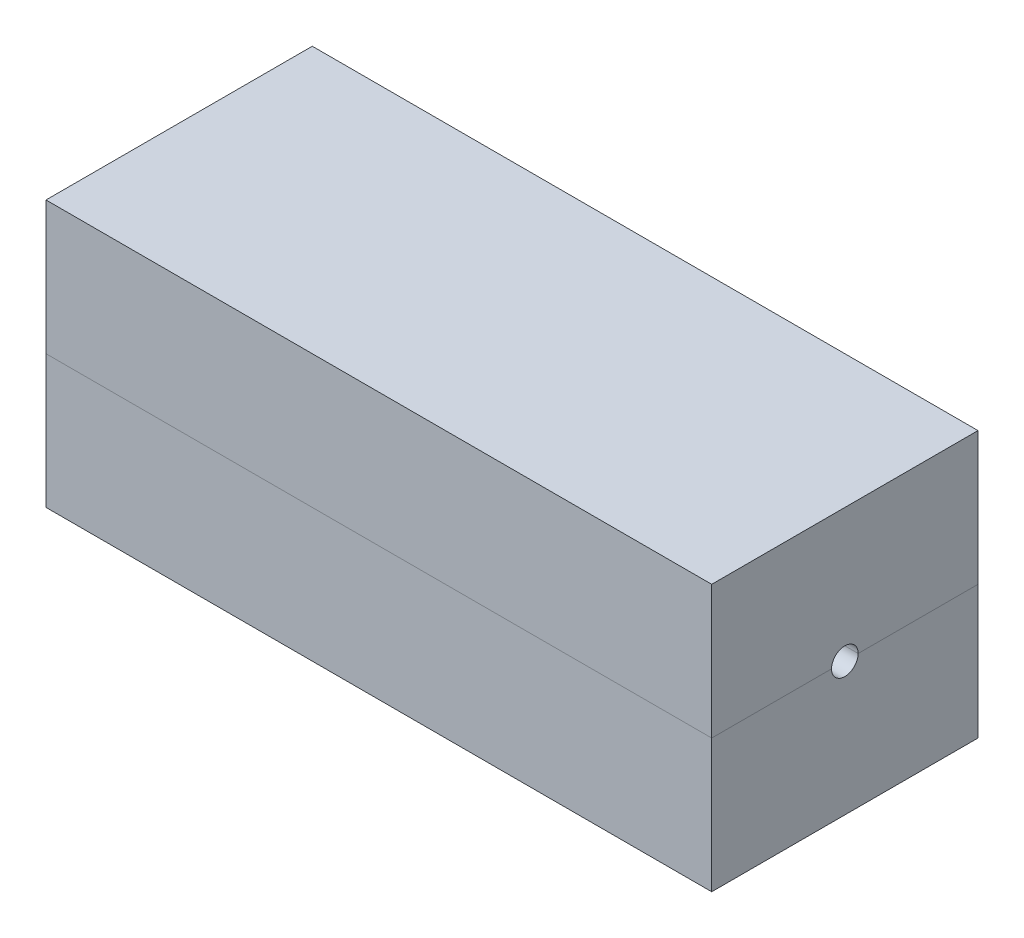
SolidWorks part; units mm, degrees
ref_plane "正面" through (0, 0, 0) normal (0, 0, 1) x (1, 0, 0)
ref_plane "平面" through (0, 0, 0) normal (0, 1, 0) x (1, 0, 0)
ref_plane "右側面" through (0, 0, 0) normal (1, 0, 0) x (0, 0, -1)
sketch "ｽｹｯﾁ1" plane through (0, 0, 0) normal (0, 0, 1) x (1, 0, 0)
  line L1 (0, 0) -> (100, 0)
  line L2 (0, 0) -> (0, 40)
  line L3 (0, 40) -> (100, 40)
  line L4 (100, 0) -> (100, 40)
  dimension "D1" = 40
  dimension "D2" = 100
extrude "ﾎﾞｽ - 押し出し1" add sketch "ｽｹｯﾁ1" along normal blind 40
ref_plane "平面1" through (0, 20, 0) normal (0, 1, 0) x (1, 0, 0)
split "部品分割1" trim tools "平面1" bodies to split 101 resulting bodies 102 103
sketch "ｽｹｯﾁ2" plane through (0, 20, 0) normal (0, 1, 0) x (1, 0, 0)
  line L0 (0, -20) -> (100, -20) construction
  line L1 (0, -40) -> (0, 0) construction
  line L2 (100, -40) -> (100, 0) construction
  line L4 (10, -30) -> (90, -30)
  line L5 (10, -30) -> (10, -10)
  line L6 (10, -10) -> (90, -10)
  line L7 (90, -30) -> (90, -10)
  line L8 (10, -30) -> (90, -10) construction
  line L9 (10, -10) -> (90, -30) construction
  point P6 (50, -20)
  dimension "D1" = 80
  dimension "D2" = 20
extrude "ｶｯﾄ - 押し出し1" cut sketch "ｽｹｯﾁ2" against normal blind 7 and the other way blind 7
sketch "ｽｹｯﾁ3" plane through (0, 20, 0) normal (0, 1, 0) x (1, 0, 0)
  line L0 (0, -20) -> (100, -20) construction
  line L1 (0, 0) -> (0, -40) construction
  line L2 (100, -40) -> (100, 0) construction
  line L4 (7.5, -32.5) -> (92.5, -32.5)
  line L6 (7.5, -7.5) -> (92.5, -7.5)
  line L8 (7.5, -32.5) -> (92.5, -7.5) construction
  line L9 (7.5, -7.5) -> (92.5, -32.5) construction
  line L10 (2.5, -37.5) -> (97.5, -37.5)
  line L12 (2.5, -2.5) -> (97.5, -2.5)
  line L14 (2.5, -37.5) -> (97.5, -2.5) construction
  line L15 (2.5, -2.5) -> (97.5, -37.5) construction
  line L20 (7.5, -7.5) -> (7.5, -15)
  line L21 (7.5, -15) -> (2.5, -15)
  line L22 (2.5, -15) -> (2.5, -2.5)
  line L23 (92.5, -7.5) -> (92.5, -15)
  line L24 (92.5, -15) -> (97.5, -15)
  line L25 (97.5, -15) -> (97.5, -2.5)
  line L26 (97.5, -15) -> (97.5, -37.5) construction
  line L27 (92.5, -15) -> (92.5, -32.5) construction
  line L28 (97.5, -25) -> (97.5, -37.5)
  line L29 (92.5, -25) -> (97.5, -25)
  line L30 (92.5, -32.5) -> (92.5, -25)
  line L31 (7.5, -32.5) -> (7.5, -25)
  line L32 (7.5, -25) -> (2.5, -25)
  line L33 (2.5, -25) -> (2.5, -37.5)
  point P6 (50, -20)
  point P11 (50, -20)
  dimension "D1" = 85
  dimension "D2" = 35
  dimension "D3" = 95
  dimension "D4" = 25
  dimension "D5" = 5
extrude "ﾎﾞｽ - 押し出し2" add sketch "ｽｹｯﾁ3" along normal blind 5
sketch "ｽｹｯﾁ4" plane through (0, 20, 0) normal (0, -1, 0) x (1, 0, 0)
  line L0 (0, 20) -> (100, 20) construction
  line L1 (0, 0) -> (0, 40) construction
  line L2 (100, 40) -> (100, 0) construction
  line L3 (92.3, 32.3) -> (92.3, 24.5)
  line L4 (7.7, 7.7) -> (92.3, 7.7)
  line L6 (7.7, 32.3) -> (92.3, 32.3)
  line L8 (7.7, 7.7) -> (92.3, 32.3) construction
  line L9 (7.7, 32.3) -> (92.3, 7.7) construction
  line L10 (2.3, 2.3) -> (97.7, 2.3)
  line L12 (2.3, 37.7) -> (97.7, 37.7)
  line L14 (2.3, 2.3) -> (97.7, 37.7) construction
  line L15 (2.3, 37.7) -> (97.7, 2.3) construction
  line L16 (92.3, 24.5) -> (97.7, 24.5)
  line L17 (97.7, 24.5) -> (97.7, 37.7)
  line L18 (7.7, 32.3) -> (7.7, 24.5)
  line L19 (7.7, 24.5) -> (2.3, 24.5)
  line L20 (2.3, 24.5) -> (2.3, 37.7)
  line L21 (92.3, 24.5) -> (92.3, 7.7) construction
  line L22 (7.7, 7.7) -> (7.7, 24.5) construction
  line L23 (97.7, 24.5) -> (97.7, 2.3) construction
  line L24 (2.3, 2.3) -> (2.3, 24.5) construction
  line L25 (97.7, 15.5) -> (97.7, 2.3)
  line L26 (92.3, 15.5) -> (97.7, 15.5)
  line L27 (92.3, 7.7) -> (92.3, 15.5)
  line L28 (2.3, 15.5) -> (2.3, 2.3)
  line L29 (7.7, 15.5) -> (2.3, 15.5)
  line L30 (7.7, 7.7) -> (7.7, 15.5)
  point P6 (50, 20)
  point P11 (50, 20)
  dimension "D1" = 24.6
  dimension "D2" = 35.4
  dimension "D3" = 84.6
  dimension "D4" = 95.4
  dimension "D5" = 4.5
  dimension "D6" = 4.5
extrude "ｶｯﾄ - 押し出し2" cut sketch "ｽｹｯﾁ4" against normal blind 5
sketch "ｽｹｯﾁ6" plane through (0, 0, 0) normal (-1, 0, 0) x (0, 0, 1)
  line L0 (0, 20) -> (40, 20) construction
  circle A0 centre (20, 20) radius 2
  dimension "D1" = 4
extrude "ｶｯﾄ - 押し出し3" cut sketch "ｽｹｯﾁ6" against normal through all
sketch "ｽｹｯﾁ7" plane through (0, 0, 0) normal (-1, 0, 0) x (0, 0, 1)
  circle A0 centre (20, 20) radius 3
  dimension "D1" = 6
extrude "ｶｯﾄ - 押し出し4" cut sketch "ｽｹｯﾁ7" against normal up to next
